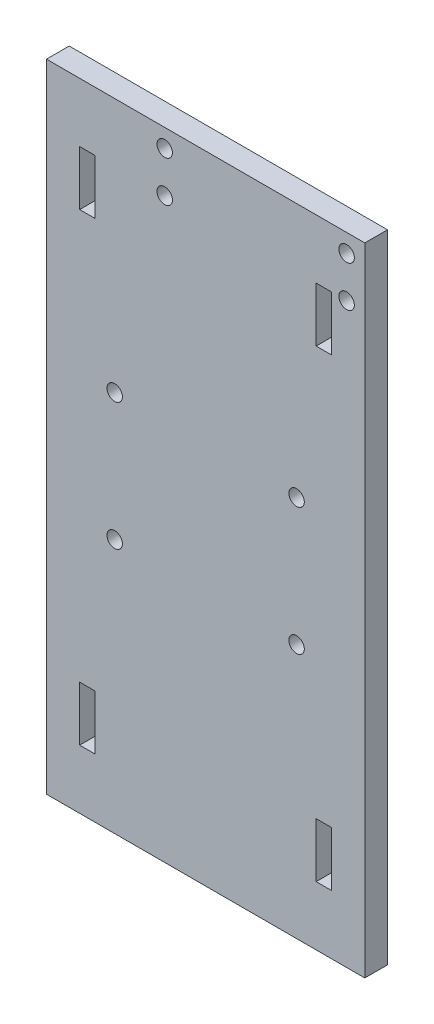
SolidWorks part; units mm, degrees
ref_plane "前视基准面" through (0, 0, 0) normal (0, 0, 1) x (1, 0, 0)
ref_plane "上视基准面" through (0, 0, 0) normal (0, 1, 0) x (1, 0, 0)
ref_plane "右视基准面" through (0, 0, 0) normal (1, 0, 0) x (0, 0, -1)
other "Configuration Table"
sketch "草图1" plane through (0, 0, 0) normal (0, 0, 1) x (1, 0, 0)
  line L1 (-35, -70) -> (35, -70)
  line L2 (-35, -70) -> (-35, 70)
  line L3 (-35, 70) -> (35, 70)
  line L4 (35, -70) -> (35, 70)
extrude "Base_70x140x5" add sketch "草图1" along normal blind 5
sketch "草图2" plane through (0, 0, 0) normal (0, 0, 1) x (1, 0, 0)
  line L1 (-27.7, -57) -> (-24.3, -57)
  line L2 (-27.7, -57) -> (-27.7, -45)
  line L3 (-27.7, -45) -> (-24.3, -45)
  line L4 (-24.3, -57) -> (-24.3, -45)
  line L6 (-27.7, 45) -> (-24.3, 45)
  line L7 (-27.7, 45) -> (-27.7, 57)
  line L8 (-27.7, 57) -> (-24.3, 57)
  line L9 (-24.3, 45) -> (-24.3, 57)
  line L11 (24.3, -57) -> (27.7, -57)
  line L12 (24.3, -57) -> (24.3, -45)
  line L13 (24.3, -45) -> (27.7, -45)
  line L14 (27.7, -57) -> (27.7, -45)
  line L16 (24.3, 45) -> (27.7, 45)
  line L17 (24.3, 45) -> (24.3, 57)
  line L18 (24.3, 57) -> (27.7, 57)
  line L19 (27.7, 45) -> (27.7, 57)
extrude "Chassis_adjustment_slots_UNVERIFIED_positions" cut sketch "草图2" against normal through all and the other way through all
sketch "草图3" plane through (0, 0, 0) normal (0, 0, 1) x (1, 0, 0)
  circle A0 centre (-20, -14) radius 1.7
  circle A1 centre (-20, 14) radius 1.7
  circle A2 centre (20, -14) radius 1.7
  circle A3 centre (20, 14) radius 1.7
  circle A4 centre (-9, 57) radius 1.7
  circle A5 centre (-9, 66) radius 1.7
  circle A6 centre (31, 57) radius 1.7
  circle A7 centre (31, 66) radius 1.7
extrude "Support_and_servo_mount_M3_clearance" cut sketch "草图3" against normal through all and the other way through all
